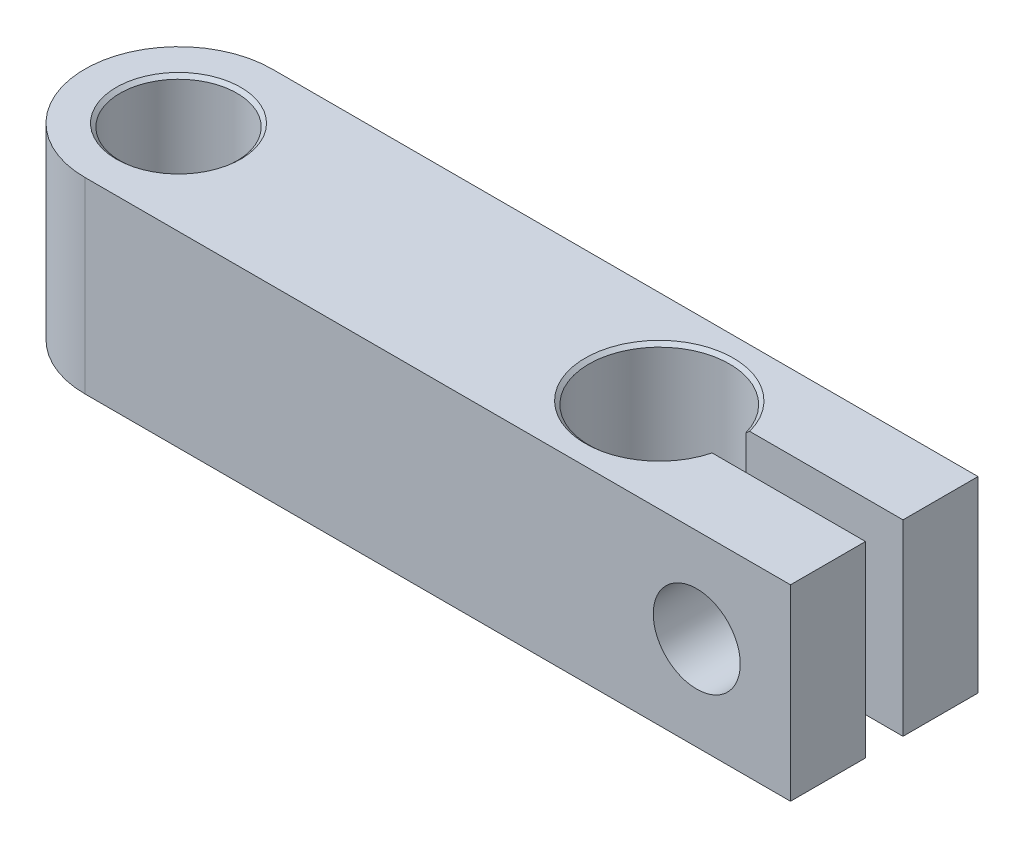
SolidWorks part; units mm, degrees
material "6061-T6 (SS)"
ref_plane "Front" through (0, 0, 0) normal (0, 0, 1) x (1, 0, 0)
ref_plane "Top" through (0, 0, 0) normal (0, 1, 0) x (1, 0, 0)
ref_plane "Right" through (0, 0, 0) normal (1, 0, 0) x (0, 0, -1)
sketch "Sketch1" plane through (0, 0, 0) normal (0, 1, 0) x (1, 0, 0)
  line L0 (23.9014, 3.175) -> (-2.5878, 3.175) construction
  line L1 (0, 0) -> (23.9014, 0)
  line L3 (0, 6.35) -> (23.9014, 6.35)
  line L4 (23.9014, 0) -> (23.9014, 6.35)
  arc A0 (0, 6.35) -> (0, 0) centre (0, 3.175) ccw
  circle A1 centre (0, 3.175) radius 1.9812
  circle A2 centre (16.2814, 3.175) radius 2.3813
  dimension "D4" = 3.9624
  dimension "D5" = 4.7625
  dimension "D1" = 16.2814
  dimension "D2" = 7.62
  dimension "D3" = 6.35
extrude "Boss-Extrude1" add sketch "Sketch1" along normal blind 6.35 contours L3 L4 L1 A0
sketch "Sketch2" plane through (0, 6.35, 0) normal (0, 1, 0) x (1, 0, 0)
  line L0 (23.9014, 0) -> (23.9014, 6.35) construction
  line L1 (16.2814, 3.81) -> (23.9014, 3.81)
  line L2 (16.2814, 3.81) -> (16.2814, 2.54)
  line L3 (16.2814, 2.54) -> (23.9014, 2.54)
  line L4 (23.9014, 3.81) -> (23.9014, 2.54)
  circle A2 centre (16.2814, 3.175) radius 2.3813 construction
  point P6 (16.2814, 3.175)
  dimension "D1" = 1.27
extrude "Cut-Extrude1" cut sketch "Sketch2" against normal through all contours L1 L4 L3 L2
chamfer "Chamfer1" distance 0.127 angle 41 4 edges at (13.9002, 0, -3.175) (0, 0, -1.1938) (13.9002, 6.35, -3.175) (0, 6.35, -1.1938)
hole_wizard "#4-40 Tapped Hole1" positions "Sketch4" profile "Sketch3" tap size "#4-40" standard "ANSI Inch"
sketch "Sketch4" plane through (0, 0, -6.35) normal (0, 0, -1) x (-1, 0, 0)
  line L0 (-23.9014, 3.175) -> (-8.0925, 3.175) construction
  line L1 (-23.9014, 6.35) -> (-23.9014, 0) construction
  point P0 (-20.7264, 3.175)
  dimension "D1" = 3.175
sketch "Sketch3" plane through (20.7264, 3.175, -6.35) normal (1, 0, 0) x (0, 1, 0)
  line L0 (0, 0) -> (0, 3.2182)
  line L1 (0, 3.2182) -> (1.1303, 2.539)
  line L2 (1.1303, 2.539) -> (1.1303, 0)
  line L5 (1.1303, 0) -> (0, 0)
  line L10 (0, 3.2182) -> (-1.1303, 2.539) construction
  line L11 (0, -6.35) -> (0, 107.95) construction
  dimension "Tap Drill Dia." = 2.2606
  dimension "Tap Drill Depth" = 2.539
  dimension "Drill Angle" = 118
cosmetic thread "Hole Thread1" parameters "D1"=2.54, "D2"=2.8448
sketch "Sketch5" plane through (0, 0, 0) normal (0, 0, 1) x (1, 0, 0)
  circle A0 centre (20.7264, 3.175) radius 1.4732
  circle A1 centre (20.7264, 3.175) radius 1.1303 construction
  dimension "D1" = 2.9464
extrude "Cut-Extrude2" cut sketch "Sketch5" against normal up to surface (2.54 mm away) contours A0 up to face at (20.391, 3.158, -2.54)
